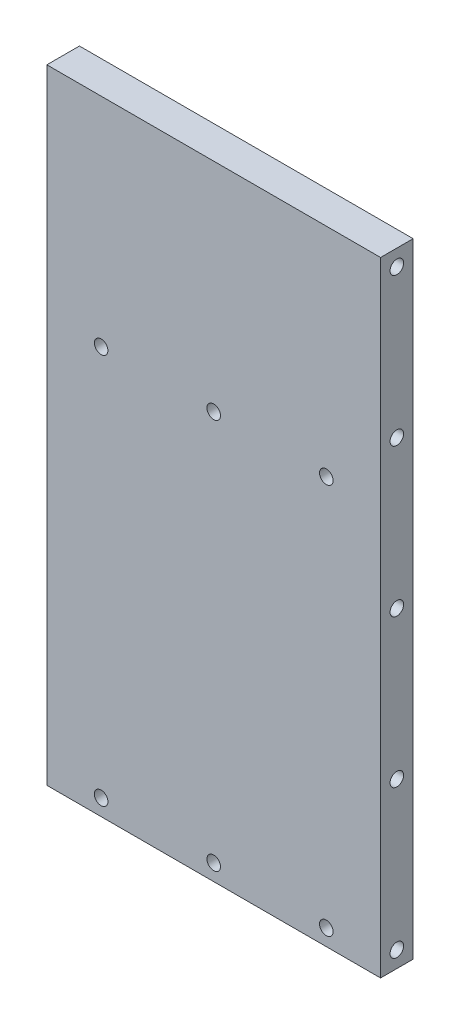
SolidWorks part; units mm, degrees
material "3.1325 (EN-AW 2017A)"
ref_plane "正面" through (0, 0, 0) normal (0, 0, 1) x (1, 0, 0)
ref_plane "平面" through (0, 0, 0) normal (0, 1, 0) x (1, 0, 0)
ref_plane "右側面" through (0, 0, 0) normal (1, 0, 0) x (0, 0, -1)
sketch "ｽｹｯﾁ1" plane through (0, 0, 0) normal (0, 0, 1) x (1, 0, 0)
  line L0 (0, 0) -> (0, -64006.4428) construction
  line L1 (-30.75, 57.5) -> (30.75, 57.5)
  line L2 (-30.75, 57.5) -> (-30.75, -57.5)
  line L3 (-30.75, -57.5) -> (30.75, -57.5)
  line L4 (30.75, 57.5) -> (30.75, -57.5)
  line L5 (0, 0) -> (50000, 0) construction
  point P8 (-20.75, 17.5)
  point P9 (0, 17.5)
  point P10 (20.75, 17.5)
  point P11 (20.75, -54.5)
  point P12 (0, -54.5)
  point P13 (-20.75, -54.5)
  point P14 (0, 54.5)
  point P17 (0, 27.25)
  point P18 (0, 0)
  point P19 (0, -27.25)
  point P20 (0, -54.5)
  dimension "D1" = 61.5
  dimension "D2" = 115
  dimension "D3" = 72
  dimension "D4" = 41.5
  dimension "D5" = 3
  dimension "D7" = 109
  dimension "D6" = 5
extrude "ﾎﾞｽ - 押し出し1" add sketch "ｽｹｯﾁ1" along normal mid plane 6
hole_wizard "M3x0.5 ねじ穴1" positions "3Dｽｹｯﾁ1" profile "ｽｹｯﾁ2" tap size "M3x0.5" standard "JIS" end condition through all
sketch3d "3Dｽｹｯﾁ1"
  point P0 (-20.75, 17.5, 3)
  point P2 (0, 17.5, 3)
  point P4 (20.75, 17.5, 3)
  point P6 (20.75, -54.5, 3)
  point P8 (0, -54.5, 3)
  point P10 (-20.75, -54.5, 3)
  point P23 (30.75, 54.5, 0)
  point P25 (30.75, 27.25, 0)
  point P27 (30.75, 0, 0)
  point P29 (30.75, -27.25, 0)
  point P31 (30.75, -54.5, 0)
  point P33 (-30.75, -54.5, 0)
  point P35 (-30.75, -27.25, 0)
  point P37 (-30.75, 0, 0)
  point P39 (-30.75, 27.25, 0)
  point P41 (-30.75, 54.5, 0)
sketch "ｽｹｯﾁ2" plane through (-20.75, 17.5, 3) normal (1, 0, 0) x (0, -1, 0)
  line L0 (0, 0) -> (0, 6)
  line L1 (0, 6) -> (1.25, 6)
  line L2 (1.25, 6) -> (1.25, 0)
  line L5 (1.25, 0) -> (0, 0)
  line L11 (0, -6.35) -> (0, 107.95) construction
  dimension "ねじ山の主要直径" = 2.5
  dimension "次ｻｰﾌｪｽまでのねじ下穴ﾄﾞﾘﾙの深さ" = 6
